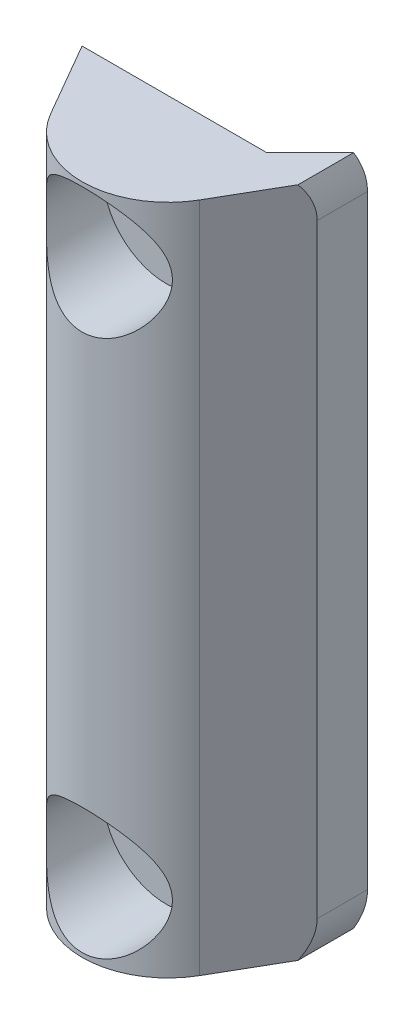
SolidWorks part; units mm, degrees
ref_plane "前视基准面" through (0, 0, 0) normal (0, 0, 1) x (1, 0, 0)
ref_plane "上视基准面" through (0, 0, 0) normal (0, 1, 0) x (1, 0, 0)
ref_plane "右视基准面" through (0, 0, 0) normal (1, 0, 0) x (0, 0, -1)
other "Configuration Table"
sketch "草图1" plane through (0, 0, 0) normal (0, 1, 0) x (1, 0, 0)
  line L0 (-4.4378, -2.5622) -> (-7, 1.8756)
  line L1 (-7, 1.8756) -> (7, 1.8756)
  line L2 (7, 1.8756) -> (4.4378, -2.5622)
  line L3 (0, 1.8756) -> (0, 0) construction
  arc A0 (-4.4378, -2.5622) -> (4.4378, -2.5622) centre (0, 0) ccw
  point P1 (0, -5.1244)
  dimension "D1" = 30
  dimension "D3" = 7
  dimension "D2" = 14
extrude "凸台-拉伸1" add sketch "草图1" along normal blind 40
sketch "草图3" plane through (0, 0, -1.8756) normal (0, 0, -1) x (-1, 0, 0)
  line L0 (-7, 0) -> (7, 0) construction
  line L1 (0, 4) -> (0, 0) construction
  line L2 (-7, 40) -> (7, 40) construction
  line L3 (0, 36) -> (0, 4) construction
  circle A0 centre (0, 4) radius 1.6
  circle A1 centre (0, 36) radius 1.6
  dimension "D1" = 3.2
  dimension "D3" = 4
  dimension "D2" = 4
extrude "切除-拉伸1" cut sketch "草图3" against normal up to next
sketch "草图4" plane through (0, 0, -1.8756) normal (0, 0, -1) x (-1, 0, 0)
  circle A0 centre (0, 4) radius 3.75
  circle A1 centre (0, 36) radius 3.75
  dimension "D1" = 7.5
extrude "切除-拉伸2" cut sketch "草图4" against normal up to next from offset 2 offset against normal yes
sketch "草图6" plane through (0, 0, -1.8756) normal (0, 0, -1) x (-1, 0, 0)
  line L7 (7, 20) -> (-7, 20) construction
  line L8 (7, 40) -> (7, 0) construction
  line L9 (-7, 40) -> (-7, 0) construction
  line L10 (-7, -3) -> (7, -3) construction
  line L11 (-7, 2) -> (-7, 0)
  line L12 (-7, 0) -> (-6.5826, 0)
  line L13 (-7, 0) -> (7, 0) construction
  line L14 (-7, 40) -> (-6.5826, 40)
  line L15 (-7, 38) -> (-7, 40)
  arc A2 (-7, 2) -> (-6.5826, 0) centre (-2, 2) ccw
  circle A3 centre (0, 4) radius 1.6 construction
  arc A4 (-7, 38) -> (-6.5826, 40) centre (-2, 38) cw
  dimension "D1" = 7
  dimension "D2" = 10
extrude "切除-拉伸3" cut sketch "草图6" against normal up to next
sketch "草图7" plane through (0, 0, 0) normal (0, 1, 0) x (1, 0, 0)
  line L0 (7, 1.8756) -> (7, 4.8756)
  line L1 (7, 1.8756) -> (6.5826, 1.8756) construction
  line L2 (6.5826, 1.1526) -> (7, 1.8756) construction
  line L3 (7, 4.8756) -> (4, 1.8756)
  line L4 (6.5826, 1.8756) -> (-7, 1.8756) construction
  line L5 (4, 1.8756) -> (7, 1.8756)
  dimension "D1" = 3
  dimension "D2" = 3
extrude "凸台-拉伸2" add sketch "草图7" along normal up to surface (40 mm away) up to face at (1.233, 40, 0.5565)
sketch "草图8" plane through (0, 0, -1.8756) normal (0, 0, 1) x (1, 0, 0)
  line L2 (7, 38) -> (7, 40)
  line L3 (7, 40) -> (6.5826, 40)
  line L4 (7, 38) -> (7, 40)
  line L5 (7, 40) -> (6.5826, 40)
  line L6 (6.5826, 0) -> (7, 0)
  line L7 (7, 0) -> (7, 2)
  line L8 (6.5826, 0) -> (7, 0)
  line L9 (7, 0) -> (7, 2)
  arc A1 (7, 38) -> (6.5826, 40) centre (2, 38) ccw
  arc A2 (7, 38) -> (6.5826, 40) centre (2, 38) ccw
  arc A3 (6.5826, 0) -> (7, 2) centre (2, 2) ccw
  arc A4 (6.5826, 0) -> (7, 2) centre (2, 2) ccw
  dimension "D1" = 0
  dimension "D2" = 0
extrude "切除-拉伸4" cut sketch "草图8" against normal up to next
